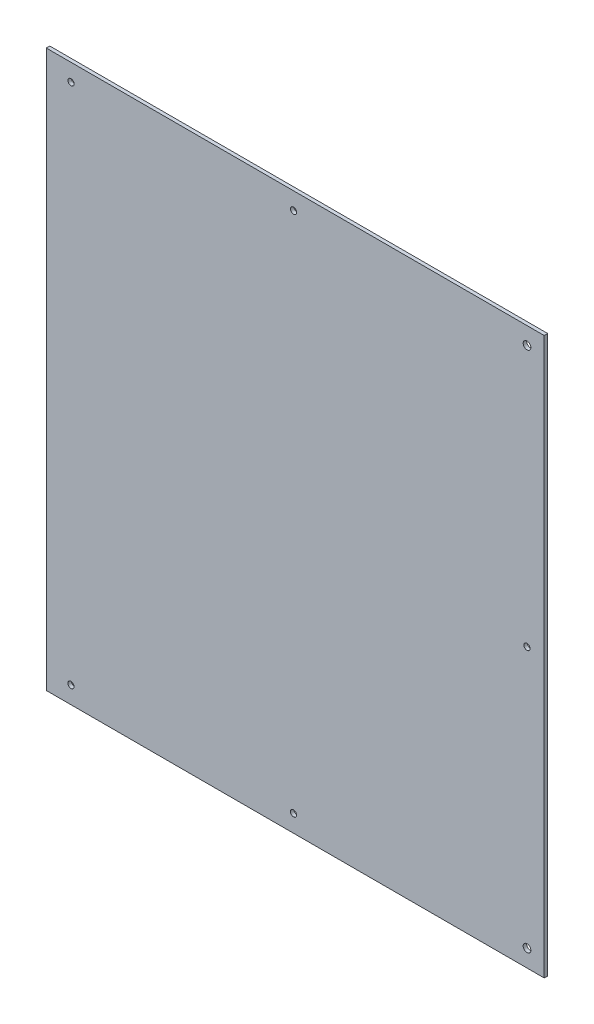
SolidWorks part; units mm, degrees
ref_plane "Front Plane" through (0, 0, 0) normal (1, 0, 0) x (0, 1, 0)
ref_plane "Top Plane" through (0, 0, 0) normal (0, 0, 1) x (0, 1, 0)
ref_plane "Right Plane" through (0, 0, 0) normal (0, 1, 0) x (-1, 0, 0)
sketch "Sketch1" plane through (0, 0, 0) normal (0, 0, 1) x (0, 1, 0)
  line L0 (-237.5, 202.5) -> (237.5, 202.5) construction
  line L1 (-250, -225) -> (250, -225)
  line L2 (-250, -225) -> (-250, 225)
  line L3 (-250, 225) -> (250, 225)
  line L4 (250, -225) -> (250, 225)
  line L5 (-250, -225) -> (250, 225) construction
  line L6 (-250, 225) -> (250, -225) construction
  line L7 (237.5, -212.5) -> (-237.5, -212.5) construction
  line L8 (237.5, -212.5) -> (237.5, 212.5) construction
  line L9 (237.5, 212.5) -> (-237.5, 212.5) construction
  line L10 (-237.5, -212.5) -> (-237.5, 212.5) construction
  line L11 (237.5, -212.5) -> (-237.5, 212.5) construction
  line L12 (237.5, 212.5) -> (-237.5, -212.5) construction
  circle A0 centre (-237.5, 212.5) radius 2.8 construction
  circle A1 centre (237.5, 212.5) radius 2.8 construction
  circle A2 centre (237.5, -212.5) radius 3.5
  circle A3 centre (-237.5, -212.5) radius 3.5
  circle A4 centre (-237.5, 202.5) radius 2.8
  circle A5 centre (237.5, 202.5) radius 2.8
  circle A6 centre (-237.5, 0) radius 2.8
  circle A7 centre (237.5, 0) radius 2.8
  circle A8 centre (0, -212.5) radius 2.8
  point P0 (0, 0)
  point P6 (0, 0)
  dimension "D3" = 7
  dimension "D4" = 5.6
  dimension "D1" = 450
  dimension "D2" = 500
  dimension "D5" = 12.5
  dimension "D6" = 12.5
  dimension "D7" = 10
extrude "Boss-Extrude1" add sketch "Sketch1" along normal blind 3.175
sketch "Sketch2" plane through (0, 0, 3.175) normal (0, 0, 1) x (1, 0, 0)
  line L1 (-225, -250) -> (228.175, -250)
  line L2 (-225, -250) -> (-225, -253.175)
  line L3 (-225, -253.175) -> (228.175, -253.175)
  line L4 (228.175, -250) -> (228.175, -253.175)
  line L5 (-225, -250) -> (228.175, -253.175) construction
  line L6 (-225, -253.175) -> (228.175, -250) construction
  line L7 (-225, 250) -> (228.175, 250)
  line L8 (-225, 250) -> (-225, 253.175)
  line L9 (-225, 253.175) -> (228.175, 253.175)
  line L10 (228.175, 250) -> (228.175, 253.175)
  line L11 (-225, 250) -> (228.175, 253.175) construction
  line L12 (-225, 253.175) -> (228.175, 250) construction
  line L13 (228.175, 250) -> (225, 250)
  line L14 (228.175, 250) -> (228.175, -250)
  line L15 (228.175, -250) -> (225, -250)
  line L16 (225, 250) -> (225, -250)
  line L17 (228.175, 250) -> (225, -250) construction
  line L18 (228.175, -250) -> (225, 250) construction
  point P4 (1.5875, -251.5875)
  point P10 (1.5875, 251.5875)
  point P15 (226.5875, 0)
  point P17 (248.9523, -250)
  line M9 (225, 250) -> (-225, 250)
  line M11 (-225, -250) -> (225, -250)
  line M12 (225, -250) -> (225, 250)
  dimension "D1" = 3.175
  dimension "D2" = 3.175
  dimension "D3" = 3.175
extrude "Boss-Extrude2" add sketch "Sketch2" against normal through all contours L4 L1 L2 L3 M11 | L14 L7 L1 M12 | L7 L10 L9 L8 M9
